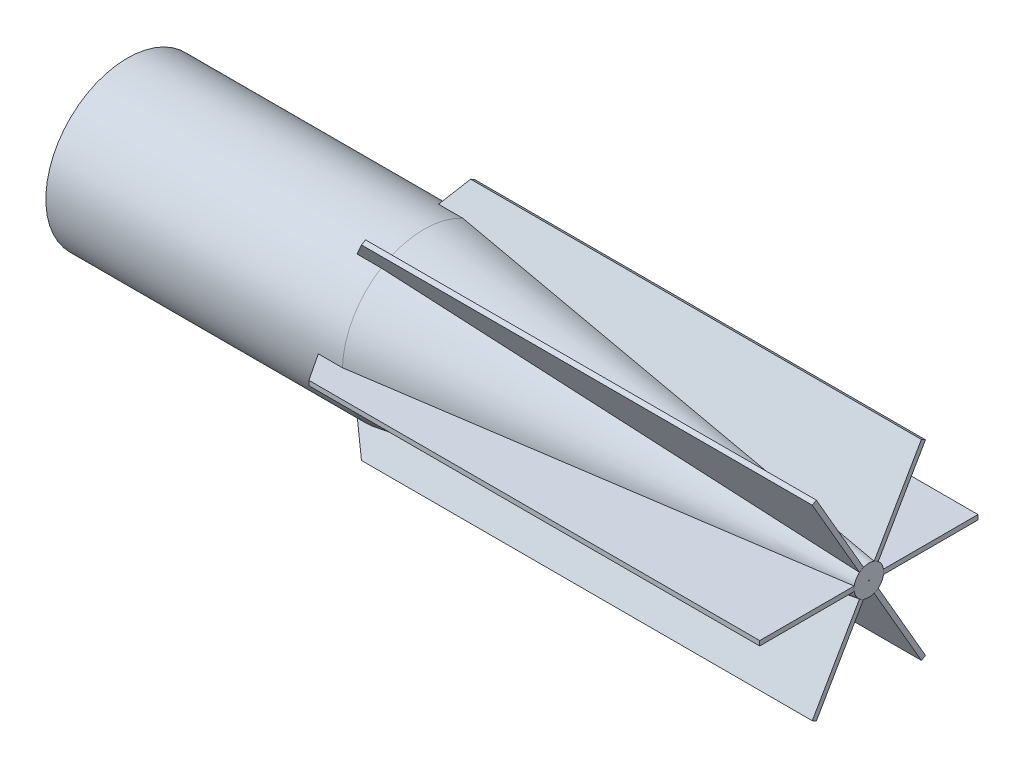
SolidWorks part; units mm, degrees
ref_plane "Front Plane" through (0, 0, 0) normal (0, 0, 1) x (1, 0, 0)
ref_plane "Top Plane" through (0, 0, 0) normal (0, 1, 0) x (1, 0, 0)
ref_plane "Right Plane" through (0, 0, 0) normal (1, 0, 0) x (0, 0, -1)
sketch "Sketch1" plane through (0, 0, 0) normal (0, 1, 0) x (1, 0, 0)
  line L0 (0, -22.5) -> (-465.3643, -22.5)
  line L1 (0, 0) -> (-250, 0)
  line L2 (0, 0) -> (0, 5)
  line L3 (0, 5) -> (-250, 5)
  line L4 (-250, 0) -> (-250, 5)
  line L5 (0, -22.5) -> (0, -17.5)
  line L6 (0, -17.5) -> (-150, 5)
  line L7 (-150, 0) -> (0, -22.5)
  line L8 (0, -22.35) -> (-1, -22.35)
  dimension "D1" = 250
  dimension "D2" = 5
  dimension "D3" = 22.5
  dimension "D4" = 5
  dimension "D5" = 150
  dimension "D6" = 1
revolve "Revolve1" add sketch "Sketch1" angle 360 about L0
sketch "Sketch3" plane through (0, 0, 0) normal (0, 1, 0) x (1, 0, 0)
  line L0 (-173, -17.5) -> (-152, 14.3)
  line L1 (0, -17.5) -> (-173, -17.5)
  line L2 (0, -17.5) -> (0, 14.3)
  line L3 (0, 14.3) -> (-173, 14.3)
  line L4 (-173, -17.5) -> (-173, 14.3)
  line L5 (0, -17.5) -> (-150, 5) construction
  line L6 (-150, 5) -> (-250, 5) construction
  line L7 (0, -17.5) -> (-150, 5)
  line L8 (-150, 5) -> (-250, 5)
  line L9 (-0.2967, -19.4779) -> (-150.1492, 3)
  line L10 (-150.1492, 3) -> (-250, 3)
  dimension "D1" = 173
  dimension "D2" = 152
  dimension "D3" = 31.8
  dimension "D4" = 2
extrude "Boss-Extrude2" add sketch "Sketch3" along normal mid plane 1.5875 contours L8 L7 L2 L3 L0 | L10 L9 L1 L7 L8 L0
pattern_circular "CirPattern1" count 6 over 360 about axis through (0, 0, 22.5) along (1, 0, 0) of "Boss-Extrude2", "Revolve1"
